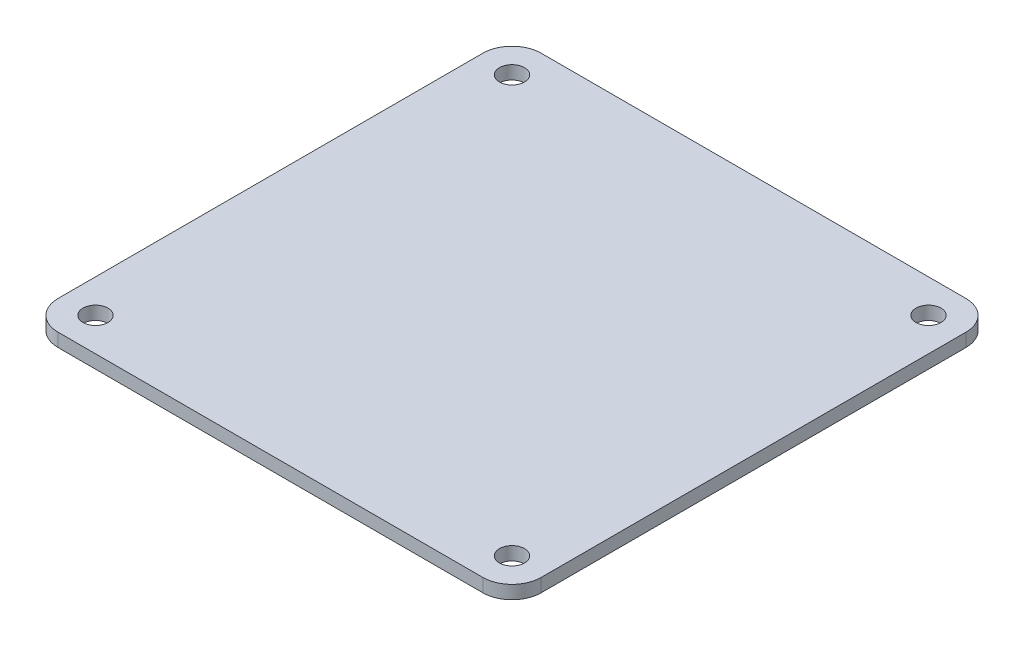
SolidWorks part; units mm, degrees
ref_plane "前视基准面" through (0, 0, 0) normal (0, 0, 1) x (1, 0, 0)
ref_plane "上视基准面" through (0, 0, 0) normal (0, 1, 0) x (1, 0, 0)
ref_plane "右视基准面" through (0, 0, 0) normal (1, 0, 0) x (0, 0, -1)
sketch "Sketch2" plane through (0, 0, 0) normal (0, 1, 0) x (1, 0, 0)
  line L0 (-29, 29) -> (29, 29)
  line L1 (-25, 25) -> (25, 25) construction
  line L2 (-25, 25) -> (-25, -25) construction
  line L3 (-25, -25) -> (25, -25) construction
  line L4 (25, 25) -> (25, -25) construction
  line L5 (-25, 25) -> (25, -25) construction
  line L6 (-25, -25) -> (25, 25) construction
  line L7 (29, 29) -> (29, -29)
  line L8 (-29, -29) -> (29, -29)
  line L9 (-29, 29) -> (-29, -29)
  line L10 (0, 0) -> (0, 14.5748) construction
  line L11 (0, 0) -> (13.9725, 0) construction
  circle A0 centre (-25, 25) radius 1.5
  circle A1 centre (25, 25) radius 1.5
  circle A2 centre (25, -25) radius 1.5
  circle A3 centre (-25, -25) radius 1.5
  point P0 (0, 0)
  dimension "D4" = 3
  dimension "D1" = 50
  dimension "D2" = 50
  dimension "D3" = 4
extrude "Boss-Extrude1" add sketch "Sketch2" along normal blind 1.6
fillet "Fillet1" radius 3.5 4 edges at (-29, 0.8, -29) (-29, 0.8, 29) (29, 0.8, -29) (29, 0.8, 29)
